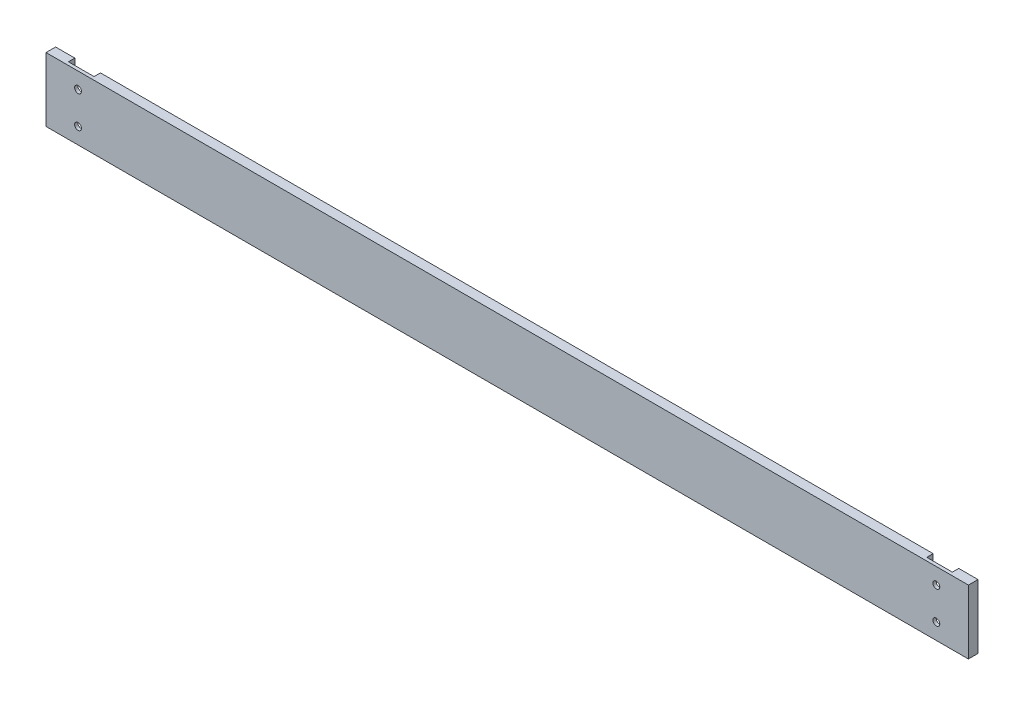
SolidWorks part; units mm, degrees
material "6061 Alloy"
ref_plane "Front Plane" through (0, 0, 0) normal (0, 0, 1) x (1, 0, 0)
ref_plane "Top Plane" through (0, 0, 0) normal (0, 1, 0) x (1, 0, 0)
ref_plane "Right Plane" through (0, 0, 0) normal (1, 0, 0) x (0, 0, -1)
sketch "Sketch1" plane through (0, 0, 0) normal (0, 1, 0) x (1, 0, 0)
  line L1 (-457.2, 0) -> (457.2, 0)
  line L2 (-457.2, 0) -> (-457.2, 9.525)
  line L3 (-457.2, 9.525) -> (457.2, 9.525)
  line L4 (457.2, 0) -> (457.2, 9.525)
  dimension "D1" = 9.525
  dimension "D2" = 914.4
extrude "Boss-Extrude1" add sketch "Sketch1" along normal blind 63.5 contours L3 L4 L1 L2
sketch "Sketch2" plane through (0, 0, -9.525) normal (0, 0, -1) x (-1, 0, 0)
  line L0 (457.2, 0) -> (-457.2, 0) construction
  line L1 (-412.75, 0) -> (-438.15, 0)
  line L2 (-412.75, 0) -> (-412.75, 63.5)
  line L3 (-412.75, 63.5) -> (-438.15, 63.5)
  line L4 (-438.15, 0) -> (-438.15, 63.5)
  line L5 (457.2, 63.5) -> (-457.2, 63.5) construction
  dimension "D1" = 25.4
  dimension "D2" = 412.75
extrude "Cut-Extrude1" cut sketch "Sketch2" against normal blind 6.35
hole_wizard "1/4 Clearance Hole1" positions "Sketch4" profile "Sketch3" hole size "1/4" standard "ANSI Inch" end condition up to next
sketch "Sketch4" plane through (0, 0, 0) normal (0, 0, 1) x (1, 0, 0)
  line L1 (-457.2, 63.5) -> (457.2, 63.5) construction
  point P6 (425.45, 47.625)
  dimension "D1" = 425.45
  dimension "D2" = 15.875
sketch "Sketch3" plane through (425.45, 47.625, 0) normal (1, 0, 0) x (0, -1, 0)
  line L0 (0, 0) -> (0, 3.175)
  line L1 (0, 3.175) -> (3.3782, 3.175)
  line L2 (3.3782, 3.175) -> (3.3782, 0)
  line L5 (3.3782, 0) -> (0, 0)
  line L11 (0, -6.35) -> (0, 107.95) construction
  dimension "Thru Hole Dia." = 6.7564
  dimension "Thru Hole Depth" = 3.175
pattern_linear "LPattern1" count 3 spacing 15.875 along (0, -1, 0) skipping (1, 0) of "1/4 Clearance Hole1"
mirror "Mirror1" about plane through (0, 0, 0) normal (1, 0, 0) of "1/4 Clearance Hole1", "LPattern1", "Cut-Extrude1"
ref_plane "Plane1" through (-425.45, 0, 0) normal (1, 0, 0) x (0, 0, -1)
ref_plane "Plane2" through (425.45, 0, 0) normal (1, 0, 0) x (0, 0, -1)
ref_plane "Plane3" through (0, 31.75, 0) normal (0, -1, 0) x (-1, 0, 0)
